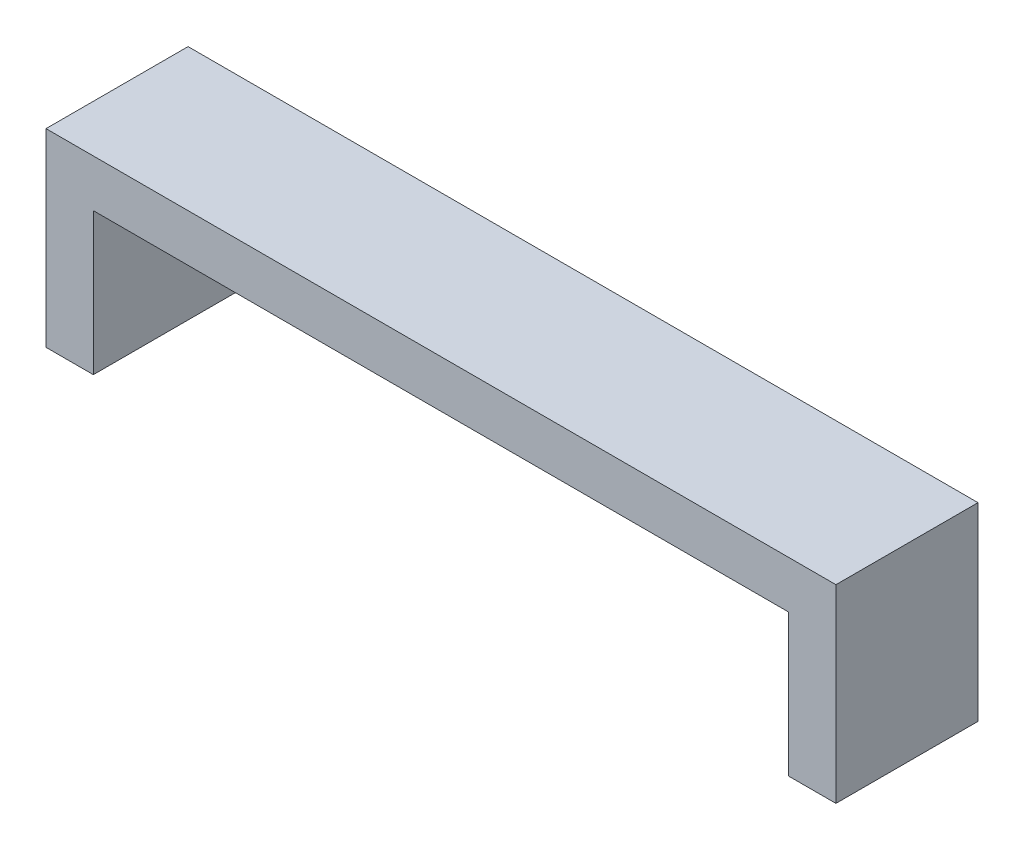
SolidWorks part; units mm, degrees
ref_plane "Front Plane" through (0, 0, 0) normal (0, 0, 1) x (1, 0, 0)
ref_plane "Top Plane" through (0, 0, 0) normal (0, 1, 0) x (1, 0, 0)
ref_plane "Right Plane" through (0, 0, 0) normal (1, 0, 0) x (0, 0, -1)
sketch "Sketch1" plane through (0, 0, 0) normal (0, 0, 1) x (1, 0, 0)
  line L1 (-26.4795, 4.7625) -> (26.4795, 4.7625)
  line L2 (-26.4795, 4.7625) -> (-26.4795, -4.7625)
  line L3 (-26.4795, -4.7625) -> (26.4795, -4.7625)
  line L4 (26.4795, 4.7625) -> (26.4795, -4.7625)
  point P4 (0, 4.7625)
  point P6 (26.4795, 0)
  dimension "D1" = 52.959
  dimension "D2" = 9.525
sketch "Sketch2" plane through (0, 0, 0) normal (0, 0, 1) x (1, 0, 0)
  line L0 (-26.4795, 4.7625) -> (-26.4795, -7.9375)
  line L1 (-26.4795, -7.9375) -> (-23.3045, -7.9375)
  line L2 (-23.3045, -7.9375) -> (-23.3045, 1.5875)
  line L3 (-23.3045, 1.5875) -> (23.3045, 1.5875)
  line L4 (23.3045, 1.5875) -> (23.3045, -7.9375)
  line L5 (23.3045, -7.9375) -> (26.4795, -7.9375)
  line L6 (26.4795, -7.9375) -> (26.4795, 4.7625)
  line L7 (26.4795, 4.7625) -> (-26.4795, 4.7625)
  line L8 (26.4795, 4.7625) -> (26.4795, -4.7625) construction
  dimension "D1" = 3.175
  dimension "D2" = 3.175
  dimension "D3" = 3.175
  dimension "D4" = 12.7
  dimension "D5" = 12.7
extrude "Boss-Extrude3" add sketch "Sketch1" along normal blind 3.175
extrude "Boss-Extrude4" add sketch "Sketch2" along normal blind 9.525
